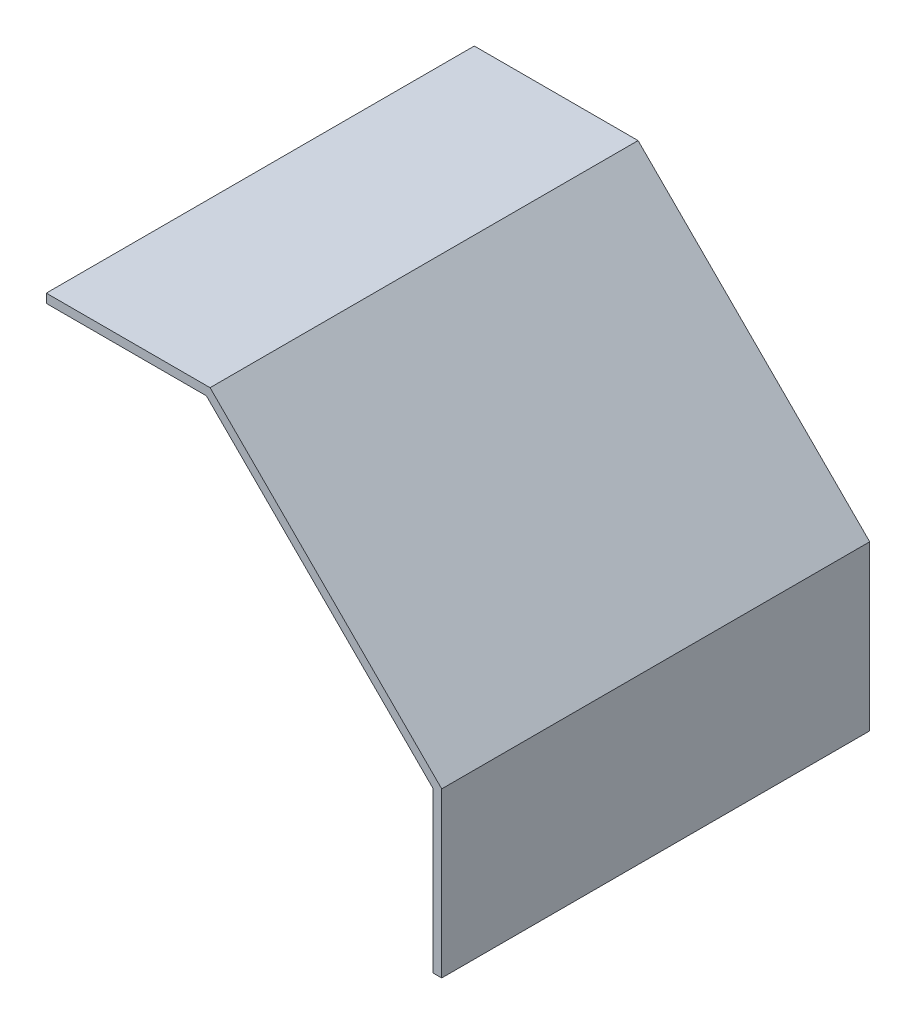
SolidWorks part; units mm, degrees
ref_plane "Front Plane" through (0, 0, 0) normal (0, 0, 1) x (1, 0, 0)
ref_plane "Top Plane" through (0, 0, 0) normal (0, 1, 0) x (1, 0, 0)
ref_plane "Right Plane" through (0, 0, 0) normal (1, 0, 0) x (0, 0, -1)
sketch "Sketch1" plane through (0, 0, 0) normal (0, 0, 1) x (1, 0, 0)
  line L0 (0, 281.5985) -> (116.6419, 281.5985) construction
  line L1 (116.6419, 281.5985) -> (281.5985, 116.6419) construction
  line L2 (281.5985, 116.6419) -> (281.5985, 0) construction
  line L3 (0, 281.5985) -> (116.6419, 281.5985)
  line L4 (116.6419, 281.5985) -> (281.5985, 116.6419)
  line L5 (281.5985, 116.6419) -> (281.5985, 0)
  line L6 (0, 275.2485) -> (114.0117, 275.2485)
  line L7 (114.0117, 275.2485) -> (275.2485, 114.0117)
  line L8 (275.2485, 114.0117) -> (275.2485, 0)
  line L9 (0, 281.5985) -> (0, 275.2485)
  line L11 (275.2485, 0) -> (281.5985, 0)
  dimension "D1" = 6.35
extrude "Boss-Extrude1" add sketch "Sketch1" along normal blind 304.8
